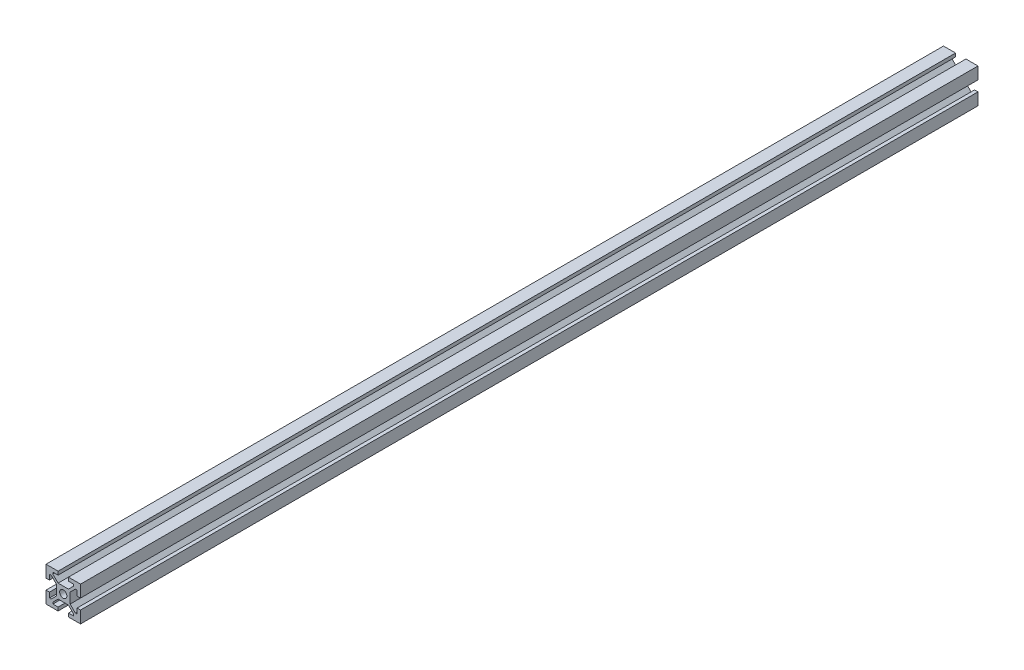
SolidWorks part; units mm, degrees
ref_plane "正面" through (0, 0, 0) normal (0, 0, 1) x (1, 0, 0)
ref_plane "平面" through (0, 0, 0) normal (0, 1, 0) x (1, 0, 0)
ref_plane "右側面" through (0, 0, 0) normal (1, 0, 0) x (0, 0, -1)
sketch "ｽｹｯﾁ2" plane through (0, 0, 0) normal (0, 0, 1) x (1, 0, 0)
  line L0 (0, 0) -> (0, 10) construction
  line L1 (-10, -10) -> (10, -10) construction
  line L2 (-10, -10) -> (-10, 10) construction
  line L3 (-10, 10) -> (10, 10) construction
  line L4 (10, -10) -> (10, 10) construction
  line L5 (-10, -10) -> (10, 10) construction
  line L6 (-10, 10) -> (10, -10) construction
  line L8 (3, 4) -> (-3, 4)
  line L9 (-6, 7) -> (6, 7) construction
  line L10 (-6, 8) -> (-6, 7)
  line L11 (6, 8) -> (6, 7)
  line L12 (-6, 7) -> (-3, 4)
  line L13 (3, 4) -> (6, 7)
  line L14 (-6, 8) -> (-3, 8)
  line L15 (-3, 8) -> (-3, 10)
  line L16 (-3, 10) -> (-10, 10)
  line L17 (6, 8) -> (3, 8)
  line L18 (3, 8) -> (3, 10)
  line L19 (3, 10) -> (10, 10)
  line L20 (7, 6) -> (4, 3)
  line L21 (4, -3) -> (4, 3)
  line L22 (4, -3) -> (7, -6)
  line L23 (8, -6) -> (8, -3)
  line L24 (8, -6) -> (7, -6)
  line L25 (8, -3) -> (10, -3)
  line L26 (10, -3) -> (10, -10)
  line L27 (8, 3) -> (10, 3)
  line L28 (10, 3) -> (10, 10)
  line L29 (8, 6) -> (8, 3)
  line L30 (8, 6) -> (7, 6)
  line L31 (6, -7) -> (3, -4)
  line L32 (-3, -4) -> (3, -4)
  line L33 (-3, -4) -> (-6, -7)
  line L34 (-6, -8) -> (-3, -8)
  line L35 (-6, -8) -> (-6, -7)
  line L36 (-3, -8) -> (-3, -10)
  line L37 (-3, -10) -> (-10, -10)
  line L38 (3, -8) -> (3, -10)
  line L39 (3, -10) -> (10, -10)
  line L40 (6, -8) -> (3, -8)
  line L41 (6, -8) -> (6, -7)
  line L42 (-7, -6) -> (-4, -3)
  line L43 (-4, 3) -> (-4, -3)
  line L44 (-4, 3) -> (-7, 6)
  line L45 (-8, 6) -> (-8, 3)
  line L46 (-8, 6) -> (-7, 6)
  line L47 (-8, 3) -> (-10, 3)
  line L48 (-10, 3) -> (-10, 10)
  line L49 (-8, -3) -> (-10, -3)
  line L50 (-10, -3) -> (-10, -10)
  line L51 (-8, -6) -> (-8, -3)
  line L52 (-8, -6) -> (-7, -6)
  circle A0 centre (0, 0) radius 2.1
  point P0 (0, 0)
  point P11 (0, 10)
  point P14 (0, 4)
  point P17 (0, 7)
  dimension "D8" = 4.2
  dimension "D1" = 20
  dimension "D2" = 6
  dimension "D3" = 2
  dimension "D4" = 4
  dimension "D5" = 12
  dimension "D6" = 6
  dimension "D7" = 4
extrude "ﾎﾞｽ - 押し出し1" add sketch "ｽｹｯﾁ2" along normal blind 520
